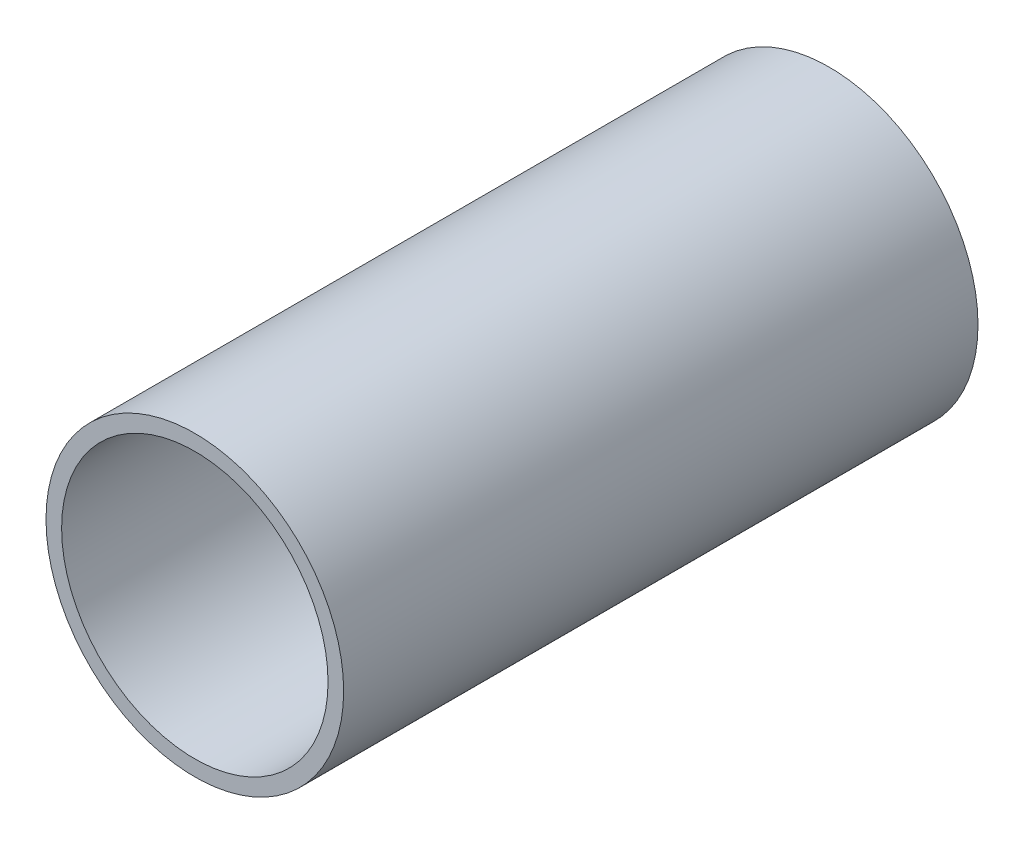
SolidWorks part; units mm, degrees
ref_plane "Front Plane" through (0, 0, 0) normal (0, 0, 1) x (1, 0, 0)
ref_plane "Top Plane" through (0, 0, 0) normal (0, 1, 0) x (1, 0, 0)
ref_plane "Right Plane" through (0, 0, 0) normal (1, 0, 0) x (0, 0, -1)
sketch "Sketch1" plane through (0, 0, 0) normal (0, 0, 1) x (1, 0, 0)
  circle A0 centre (0, 0) radius 15.25
  circle A1 centre (0, 0) radius 13.65
  dimension "D1" = 30.5
  dimension "D2" = 1.6
extrude "Boss-Extrude1" add sketch "Sketch1" along normal blind 65
